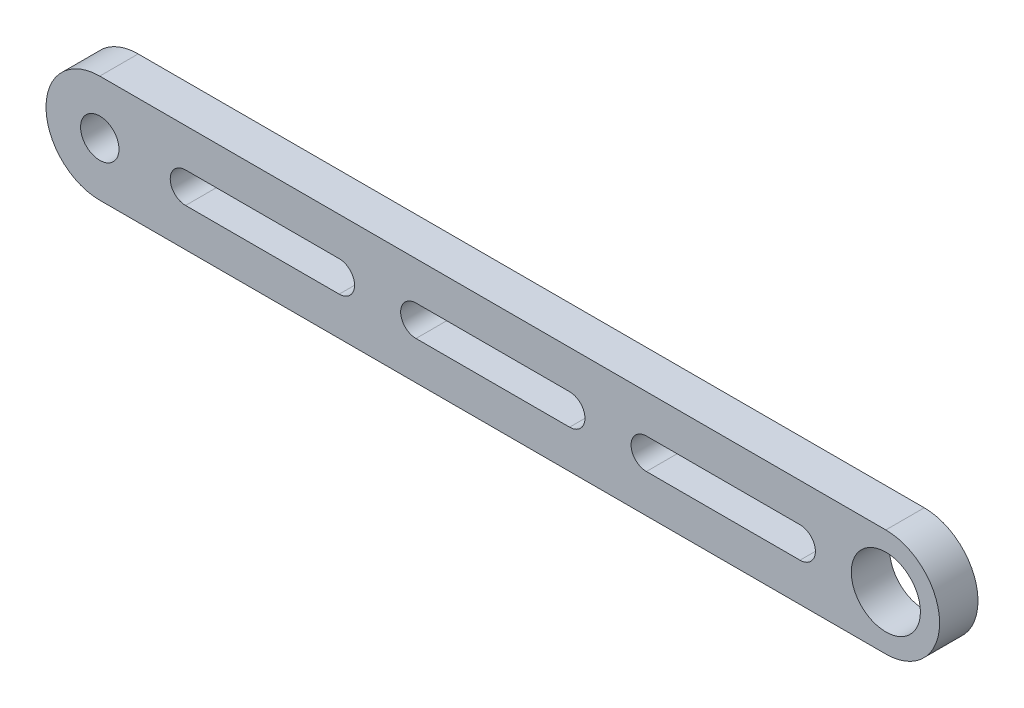
SolidWorks part; units mm, degrees
material "Thornel Mat VMA"
ref_plane "前视基准面" through (0, 0, 0) normal (0, 0, 1) x (1, 0, 0)
ref_plane "上视基准面" through (0, 0, 0) normal (0, 1, 0) x (1, 0, 0)
ref_plane "右视基准面" through (0, 0, 0) normal (1, 0, 0) x (0, 0, -1)
sketch "草图2" plane through (0, 0, 0) normal (0, 0, 1) x (1, 0, 0)
  line L0 (-51.175, 0) -> (51.175, 0) construction
  line L1 (-51.175, 7) -> (51.175, 7)
  line L2 (-51.175, -7) -> (51.175, -7)
  arc A0 (-51.175, 7) -> (-51.175, -7) centre (-51.175, 0) ccw
  arc A1 (51.175, -7) -> (51.175, 7) centre (51.175, 0) ccw
  circle A2 centre (51.175, 0) radius 4.5
  circle A3 centre (-51.175, 0) radius 4.5
  point P2 (0, 0)
  dimension "D2" = 7
  dimension "D3" = 9
  dimension "D1" = 102.35
extrude "凸台-拉伸1" add sketch "草图2" along normal mid plane 5
sketch "草图3" plane through (0, 0, 2.5) normal (0, 0, 1) x (1, 0, 0)
  line L0 (-10, 0) -> (10, 0) construction
  line L1 (-10, 2) -> (10, 2)
  line L2 (-10, -2) -> (10, -2)
  arc A0 (-10, 2) -> (-10, -2) centre (-10, 0) ccw
  arc A1 (10, -2) -> (10, 2) centre (10, 0) ccw
  point P2 (0, 0)
  dimension "D2" = 2
  dimension "D1" = 20
extrude "切除-拉伸1" cut sketch "草图3" against normal blind 10
pattern_linear "阵列(线性)1" count 2 spacing 30 along (-1, 0, 0) count 2 spacing 30 along (1, 0, 0) of "切除-拉伸1"
sketch "草图5" plane through (0, 0, 2.5) normal (0, 0, 1) x (1, 0, 0)
  circle A0 centre (-51.175, 0) radius 2.5
  circle A1 centre (-51.175, 0) radius 4.5 construction
  circle A2 centre (-51.175, 0) radius 4.5
  dimension "D1" = 5
extrude "凸台-拉伸3" add sketch "草图5" against normal up to surface (5 mm away) up to face at (-30, 0, -2.5)
